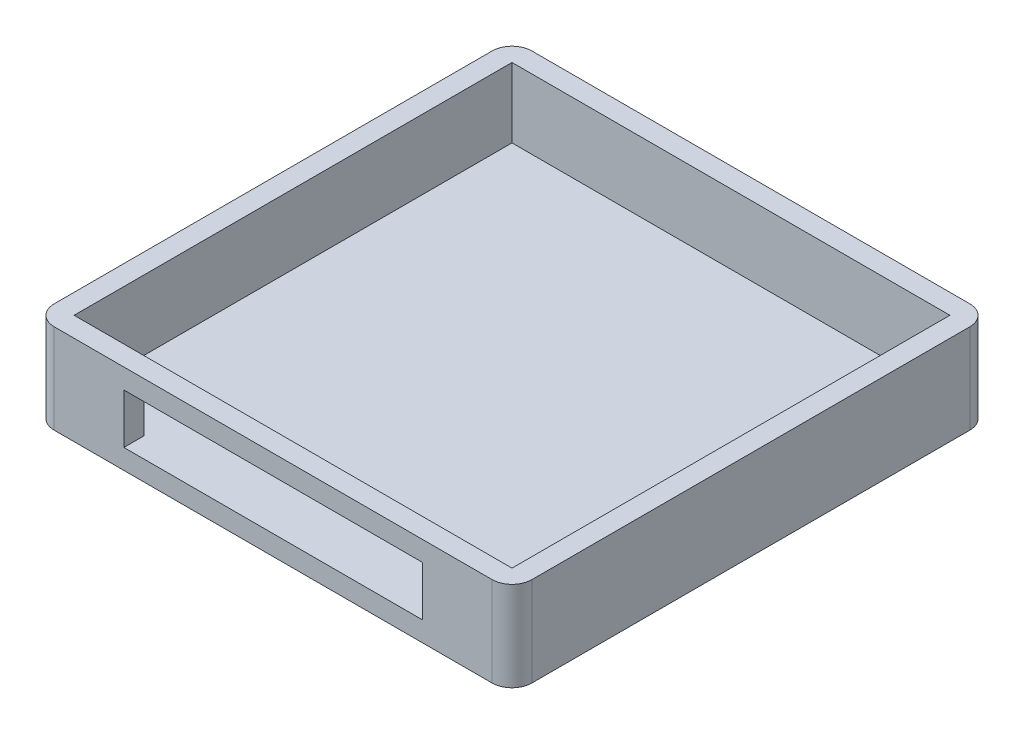
SolidWorks part; units mm, degrees
ref_plane "Front Plane" through (0, 0, 0) normal (0, 0, 1) x (1, 0, 0)
ref_plane "Top Plane" through (0, 0, 0) normal (0, 1, 0) x (1, 0, 0)
ref_plane "Right Plane" through (0, 0, 0) normal (1, 0, 0) x (0, 0, -1)
sketch "Sketch1" plane through (0, 0, 0) normal (0, 1, 0) x (1, 0, 0)
  line L1 (-24, 24) -> (24, 24)
  line L2 (-24, 24) -> (-24, -24)
  line L3 (-24, -24) -> (24, -24)
  line L4 (24, 24) -> (24, -24)
  line L5 (-24, 24) -> (24, -24) construction
  line L6 (-24, -24) -> (24, 24) construction
  point P0 (0, 0)
  dimension "D1" = 48
  dimension "D2" = 48
extrude "Boss-Extrude1" add sketch "Sketch1" along normal blind 9
sketch "Sketch2" plane through (0, 9, 0) normal (0, 1, 0) x (1, 0, 0)
  line L1 (-22, 22) -> (22, 22)
  line L2 (-22, 22) -> (-22, -22)
  line L3 (-22, -22) -> (22, -22)
  line L4 (22, 22) -> (22, -22)
  line L5 (-22, 22) -> (22, -22) construction
  line L6 (-22, -22) -> (22, 22) construction
  point P0 (0, 0)
  dimension "D1" = 44
  dimension "D2" = 44
extrude "Cut-Extrude1" cut sketch "Sketch2" against normal blind 7
sketch "Sketch3" plane through (0, 0, 0) normal (0, -1, 0) x (1, 0, 0)
  circle A0 centre (0, 0) radius 6
  dimension "D1" = 12
extrude "Boss-Extrude2" add sketch "Sketch3" along normal blind 10
sketch "Sketch4" plane through (0, -10, 0) normal (0, -1, 0) x (1, 0, 0)
  circle A0 centre (0, 0) radius 3.6
  dimension "D1" = 7.2
extrude "Cut-Extrude2" cut sketch "Sketch4" against normal up to surface (10 mm away) up to face at (0, 0, -6)
sketch "Sketch5" plane through (0, 0, 24) normal (0, 0, 1) x (1, 0, 0)
  line L0 (-24, 0) -> (24, 0) construction
  line L1 (-15, 7) -> (15, 7)
  line L2 (-15, 7) -> (-15, 2)
  line L3 (-15, 2) -> (15, 2)
  line L4 (15, 7) -> (15, 2)
  line L5 (-15, 7) -> (15, 2) construction
  line L6 (-15, 2) -> (15, 7) construction
  line L7 (24, 9) -> (24, 0) construction
  point P0 (0, 4.5)
  dimension "D1" = 2
  dimension "D2" = 5
  dimension "D3" = 30
  dimension "D4" = 9
extrude "Cut-Extrude3" cut sketch "Sketch5" against normal blind 10
fillet "Fillet1" radius 2 4 edges at (-24, 4.5, -24) (24, 4.5, -24) (-24, 4.5, 24) (24, 4.5, 24)
